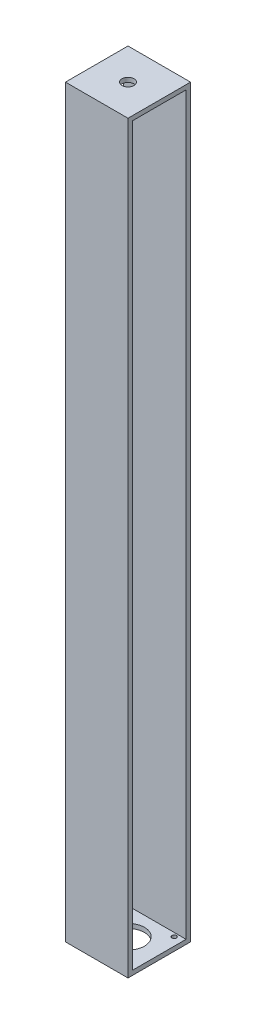
SolidWorks part; units mm, degrees
ref_plane "前视" through (0, 0, 0) normal (0, 0, 1) x (1, 0, 0)
ref_plane "上视" through (0, 0, 0) normal (0, 1, 0) x (1, 0, 0)
ref_plane "右视" through (0, 0, 0) normal (1, 0, 0) x (0, 0, -1)
sketch "草图1" plane through (0, 0, 0) normal (0, 1, 0) x (1, 0, 0)
  line L1 (0, 0) -> (42, 0)
  line L2 (0, 0) -> (0, -42)
  line L3 (0, -42) -> (42, -42)
  line L4 (42, 0) -> (42, -42)
  dimension "D1" = 42
  dimension "D2" = 42
extrude "凸台-拉伸1" add sketch "草图1" along normal blind 500
sketch "草图2" plane through (0, 0, 0) normal (0, -1, 0) x (1, 0, 0)
  line L0 (42, 0) -> (0, 0) construction
  line L1 (0, 0) -> (0, 42) construction
  line L2 (21, 42) -> (21, 21) construction
  line L3 (0, 42) -> (42, 42) construction
  line L4 (0, 21) -> (21, 21) construction
  circle A0 centre (21, 21) radius 11
  circle A1 centre (5.5, 5.5) radius 1.5
  circle A2 centre (5.5, 36.5) radius 1.5
  circle A3 centre (36.5, 5.5) radius 1.5
  circle A4 centre (36.5, 36.5) radius 1.5
  dimension "D1" = 22
  dimension "D4" = 3
  dimension "D2" = 5.5
  dimension "D3" = 5.5
extrude "切除-拉伸1" cut sketch "草图2" against normal blind 3
sketch "草图3" plane through (0, 500, 0) normal (0, 1, 0) x (1, 0, 0)
  circle A0 centre (21, -21) radius 4
  dimension "D1" = 8
extrude "切除-拉伸2" cut sketch "草图3" against normal blind 3
sketch "草图4" plane through (0, 0, 0) normal (1, 0, 0) x (0, 0, -1)
  line L0 (0, 500) -> (0, 0) construction
  line L1 (-39, 497) -> (-3, 497)
  line L2 (-39, 497) -> (-39, 3)
  line L3 (-39, 3) -> (-3, 3)
  line L4 (-3, 497) -> (-3, 3)
  line L5 (-42, 500) -> (-42, 0) construction
  line L6 (-42, 0) -> (0, 0) construction
  line L7 (-42, 500) -> (0, 500) construction
  dimension "D1" = 3
  dimension "D2" = 3
  dimension "D3" = 3
  dimension "D4" = 3
extrude "切除-拉伸3" cut sketch "草图4" along normal through all
